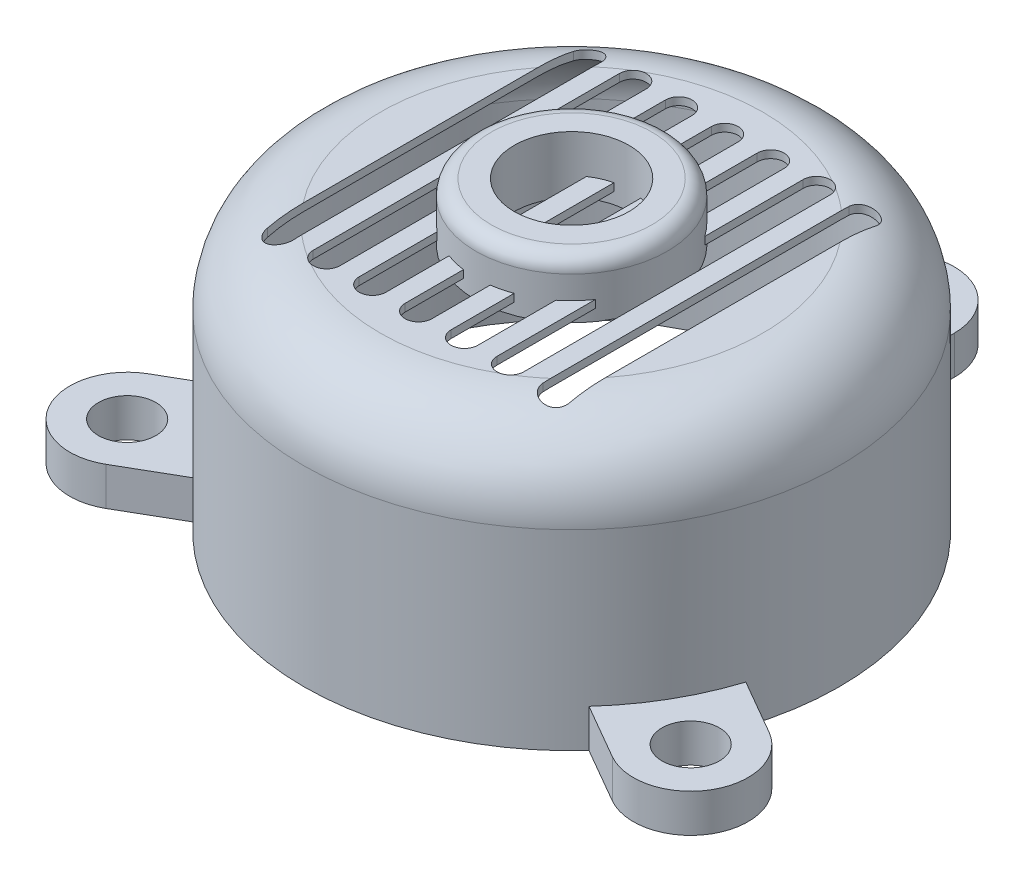
SolidWorks part; units mm, degrees
ref_plane "Front Plane" through (0, 0, 0) normal (0, 0, 1) x (1, 0, 0)
ref_plane "Top Plane" through (0, 0, 0) normal (0, 1, 0) x (1, 0, 0)
ref_plane "Right Plane" through (0, 0, 0) normal (1, 0, 0) x (0, 0, -1)
sketch "Sketch2" plane through (0, 0, 0) normal (0, 0, 1) x (1, 0, 0)
  line L0 (0, 0) -> (0, 99599.7168) construction
  line L1 (0, 0) -> (99599.7168, 0) construction
  line L2 (0, 88.9) -> (63.5, 88.9)
  line L3 (88.9, 63.5) -> (88.9, 0)
  arc A0 (63.5, 88.9) -> (88.9, 63.5) centre (63.5, 63.5) cw
  point P9 (0, 0)
  dimension "D1" = 177.8
  dimension "D2" = 25.4
  dimension "D3" = 63.5
revolve "Revolve-Thin1" add sketch "Sketch2" angle 360 about L0
sketch "Sketch3" plane through (0, 88.9, 0) normal (0, 1, 0) x (1, 0, 0)
  line L0 (-19.05, 86.8349) -> (-19.05, 107.95)
  line L1 (19.05, 107.95) -> (19.05, 86.8349)
  line L2 (84.7263, -26.9197) -> (103.0124, -37.4772)
  line L3 (83.9624, -70.4728) -> (65.6763, -59.9153)
  line L4 (-65.6763, -59.9153) -> (-83.9624, -70.4728)
  line L5 (-103.0124, -37.4772) -> (-84.7263, -26.9197)
  circle A0 centre (0, 0) radius 107.95 construction
  circle A1 centre (0, 0) radius 88.9 construction
  circle A2 centre (0, 0) radius 88.9
  arc A3 (-19.05, 107.95) -> (19.05, 107.95) centre (0, 107.95) cw
  circle A4 centre (0, 107.95) radius 9.525
  arc A5 (103.0124, -37.4772) -> (83.9624, -70.4728) centre (93.4874, -53.975) cw
  circle A6 centre (93.4874, -53.975) radius 9.525
  arc A7 (-83.9624, -70.4728) -> (-103.0124, -37.4772) centre (-93.4874, -53.975) cw
  circle A8 centre (-93.4874, -53.975) radius 9.525
  point P10 (0, 0)
  point P12 (0, 0)
  point P27 (0, 0)
  dimension "D1" = 215.9
  dimension "D2" = 19.05
  dimension "D3" = 19.05
  dimension "D4" = 3
extrude "Boss-Extrude1" add sketch "Sketch3" along normal blind 12.7 from offset 88.9 contours A7 L4 A2 L5 A8 | A3 L0 A2 L1 A4 | A5 L2 A2 L3 A6 offset against normal yes
sketch "Sketch4" plane through (0, 88.9, 0) normal (0, 1, 0) x (1, 0, 0)
  line L0 (-45.72, -50.8) -> (-45.72, 50.8) construction
  line L1 (-50.165, -50.8) -> (-50.165, 50.8)
  line L2 (-41.275, -50.8) -> (-41.275, 50.8)
  line L3 (-30.48, -50.8) -> (-30.48, 50.8) construction
  line L4 (-34.925, -50.8) -> (-34.925, 50.8)
  line L5 (-26.035, -50.8) -> (-26.035, 50.8)
  line L6 (-15.24, -50.8) -> (-15.24, 50.8) construction
  line L7 (-19.685, -50.8) -> (-19.685, 50.8)
  line L8 (-10.795, -50.8) -> (-10.795, 50.8)
  line L9 (0, -50.8) -> (0, 50.8) construction
  line L10 (-4.445, -50.8) -> (-4.445, 50.8)
  line L11 (4.445, -50.8) -> (4.445, 50.8)
  line L12 (15.24, -50.8) -> (15.24, 50.8) construction
  line L13 (10.795, -50.8) -> (10.795, 50.8)
  line L14 (19.685, -50.8) -> (19.685, 50.8)
  line L15 (30.48, -50.8) -> (30.48, 50.8) construction
  line L16 (26.035, -50.8) -> (26.035, 50.8)
  line L17 (34.925, -50.8) -> (34.925, 50.8)
  line L18 (45.72, -50.8) -> (45.72, 50.8) construction
  line L19 (41.275, -50.8) -> (41.275, 50.8)
  line L20 (50.165, -50.8) -> (50.165, 50.8)
  arc A0 (-50.165, -50.8) -> (-41.275, -50.8) centre (-45.72, -50.8) ccw
  arc A1 (-41.275, 50.8) -> (-50.165, 50.8) centre (-45.72, 50.8) ccw
  arc A2 (-34.925, -50.8) -> (-26.035, -50.8) centre (-30.48, -50.8) ccw
  arc A3 (-26.035, 50.8) -> (-34.925, 50.8) centre (-30.48, 50.8) ccw
  arc A4 (-19.685, -50.8) -> (-10.795, -50.8) centre (-15.24, -50.8) ccw
  arc A5 (-10.795, 50.8) -> (-19.685, 50.8) centre (-15.24, 50.8) ccw
  arc A6 (-4.445, -50.8) -> (4.445, -50.8) centre (0, -50.8) ccw
  arc A7 (4.445, 50.8) -> (-4.445, 50.8) centre (0, 50.8) ccw
  arc A8 (10.795, -50.8) -> (19.685, -50.8) centre (15.24, -50.8) ccw
  arc A9 (19.685, 50.8) -> (10.795, 50.8) centre (15.24, 50.8) ccw
  arc A10 (26.035, -50.8) -> (34.925, -50.8) centre (30.48, -50.8) ccw
  arc A11 (34.925, 50.8) -> (26.035, 50.8) centre (30.48, 50.8) ccw
  arc A12 (41.275, -50.8) -> (50.165, -50.8) centre (45.72, -50.8) ccw
  arc A13 (50.165, 50.8) -> (41.275, 50.8) centre (45.72, 50.8) ccw
  point P2 (-45.72, 0)
  point P11 (-30.48, 0)
  point P18 (-15.24, 0)
  point P25 (0, 0)
  point P32 (15.24, 0)
  point P39 (30.48, 0)
  point P46 (45.72, 0)
  dimension "D1" = 8.89
  dimension "D2" = 45.72
  dimension "D3" = 101.6
  dimension "D4" = 7
extrude "Cut-Extrude1" cut sketch "Sketch4" against normal through all
sketch "Sketch5" plane through (0, 88.9, 0) normal (0, 1, 0) x (1, 0, 0)
  circle A0 centre (0, 0) radius 31.75
  circle A1 centre (0, 0) radius 19.05
  dimension "D1" = 63.5
  dimension "D2" = 38.1
extrude "Boss-Extrude2" add sketch "Sketch5" along normal blind 12.7 and the other way blind 6.35
fillet "Fillet1" radius 5.08 1 edges at (0, 101.6, 31.75)
